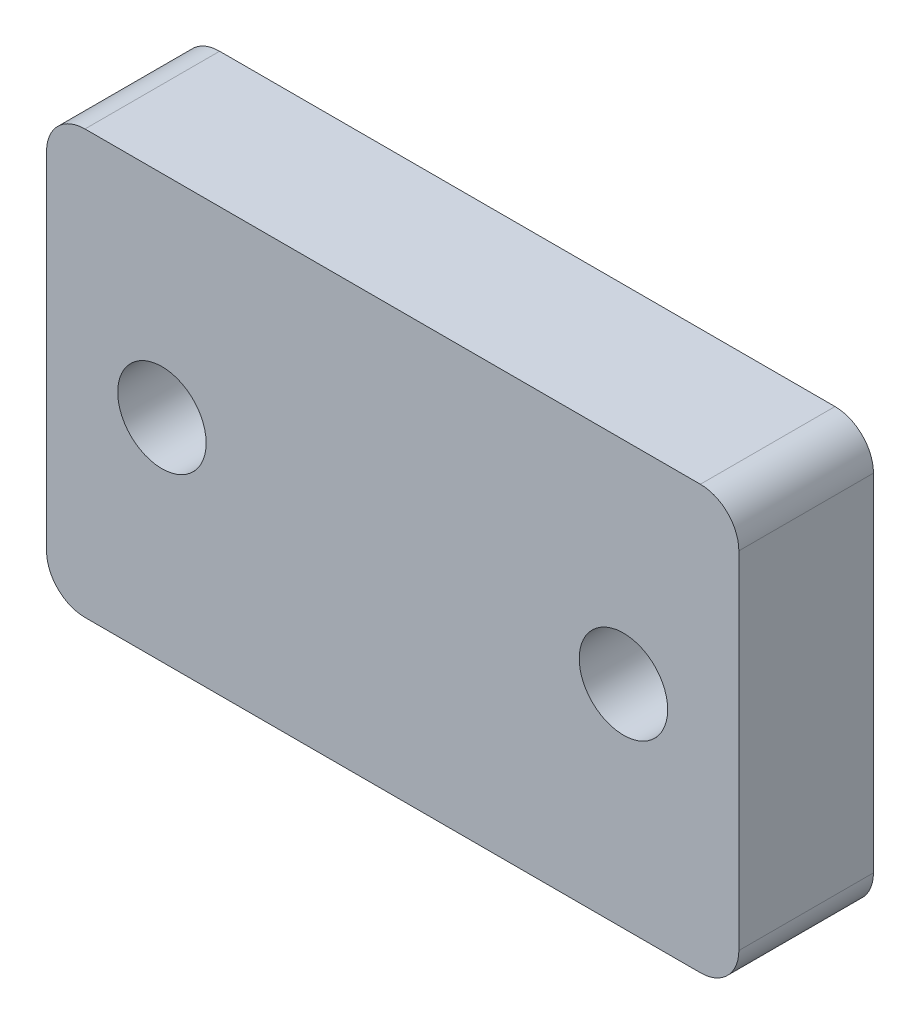
SolidWorks part; units mm, degrees
ref_plane "前视基准面" through (0, 0, 0) normal (0, 0, 1) x (1, 0, 0)
ref_plane "上视基准面" through (0, 0, 0) normal (0, 1, 0) x (1, 0, 0)
ref_plane "右视基准面" through (0, 0, 0) normal (1, 0, 0) x (0, 0, -1)
sketch "草图1" plane through (0, 0, 0) normal (0, 0, 1) x (1, 0, 0)
  line L1 (0, 0) -> (18, 0)
  line L2 (0, 0) -> (0, 11)
  line L3 (0, 11) -> (18, 11)
  line L4 (18, 0) -> (18, 11)
  circle A0 centre (3, 5.5) radius 1.15
  circle A1 centre (15, 5.5) radius 1.15
  dimension "D3" = 2.3
  dimension "D4" = 2.3
  dimension "D5" = 5.5
  dimension "D6" = 3
  dimension "D7" = 3
  dimension "D1" = 11
  dimension "D2" = 18
extrude "凸台-拉伸1" add sketch "草图1" along normal blind 3.5
fillet "圆角1" radius 1 4 edges at (18, 11, 1.75) (0, 11, 1.75) (18, 0, 1.75) (0, 0, 1.75)
